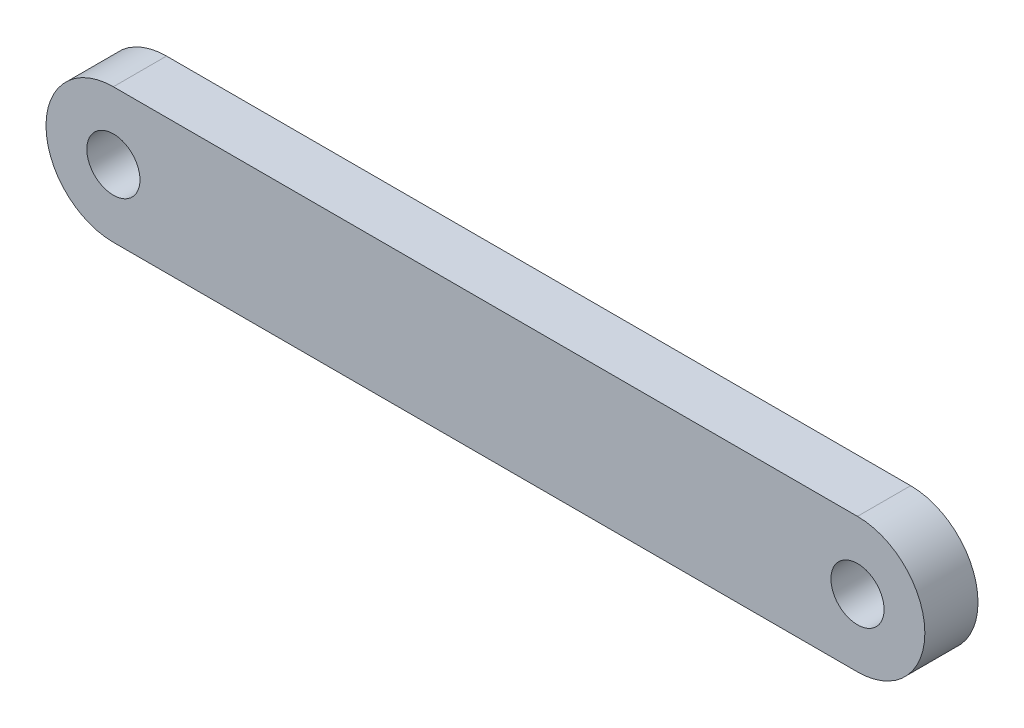
SolidWorks part; units mm, degrees
ref_plane "Front Plane" through (0, 0, 0) normal (0, 0, 1) x (1, 0, 0)
ref_plane "Top Plane" through (0, 0, 0) normal (0, 1, 0) x (1, 0, 0)
ref_plane "Right Plane" through (0, 0, 0) normal (1, 0, 0) x (0, 0, -1)
sketch "Sketch1" plane through (0, 0, 0) normal (0, 0, 1) x (1, 0, 0)
  line L0 (-13.0251, 0) -> (14.9749, 0) construction
  line L1 (-13.0251, 2.5348) -> (14.9749, 2.5348)
  line L2 (-13.0251, -2.5348) -> (14.9749, -2.5348)
  arc A0 (-13.0251, 2.5348) -> (-13.0251, -2.5348) centre (-13.0251, 0) ccw
  arc A1 (14.9749, -2.5348) -> (14.9749, 2.5348) centre (14.9749, 0) ccw
  circle A2 centre (14.9749, 0) radius 1
  circle A3 centre (-13.0251, 0) radius 1
  point P3 (0.9749, 0)
  dimension "D1" = 28
extrude "Boss-Extrude1" add sketch "Sketch1" along normal blind 2
